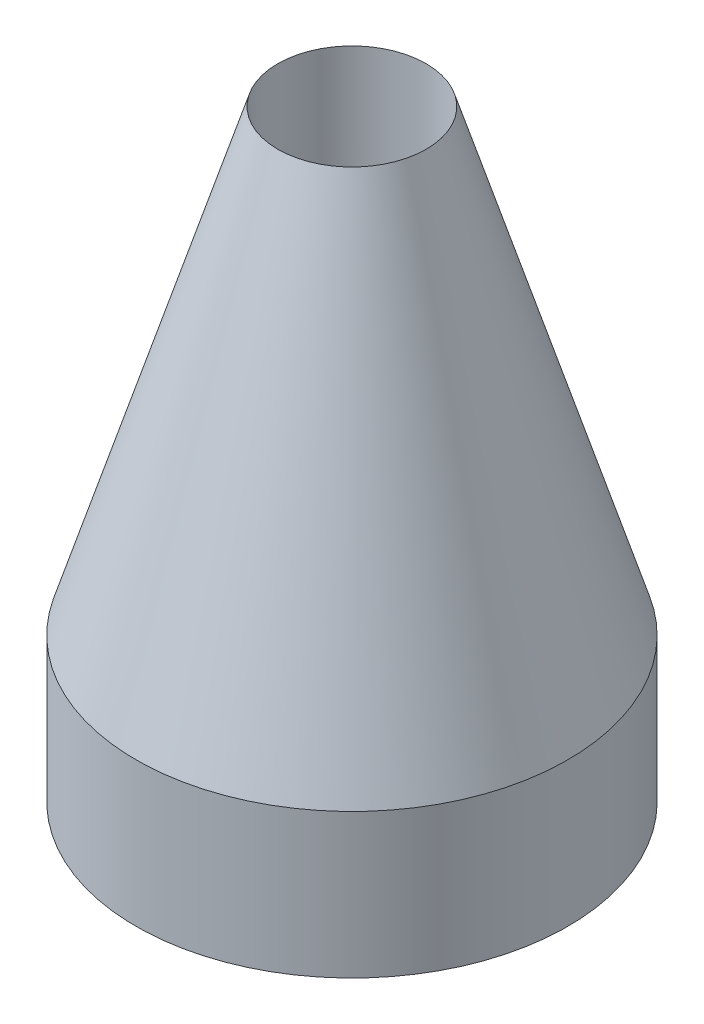
SolidWorks part; units mm, degrees
material "Silicon Rubber"
ref_plane "Front Plane" through (0, 0, 0) normal (0, 0, 1) x (1, 0, 0)
ref_plane "Top Plane" through (0, 0, 0) normal (0, 1, 0) x (1, 0, 0)
ref_plane "Right Plane" through (0, 0, 0) normal (1, 0, 0) x (0, 0, -1)
sketch "Sketch1" plane through (0, 0, 0) normal (0, 0, 1) x (1, 0, 0)
  line L0 (0, -29.4262) -> (41.4535, -29.4262)
  line L1 (41.4535, -29.4262) -> (41.4535, -1.7162)
  line L2 (0, -29.4262) -> (0, 86.2538)
  line L4 (0, 86.2538) -> (14.25, 86.2538)
  line L5 (14.25, 86.2538) -> (41.4535, -1.7162)
revolve "Revolve2" add sketch "Sketch1" angle 360 about L2
sketch "Sketch2" plane through (0, 86.2538, 0) normal (0, 1, 0) x (1, 0, 0)
  circle A0 centre (0, 0) radius 14.25
extrude "Cut-Extrude1" cut sketch "Sketch2" against normal blind 87.71
